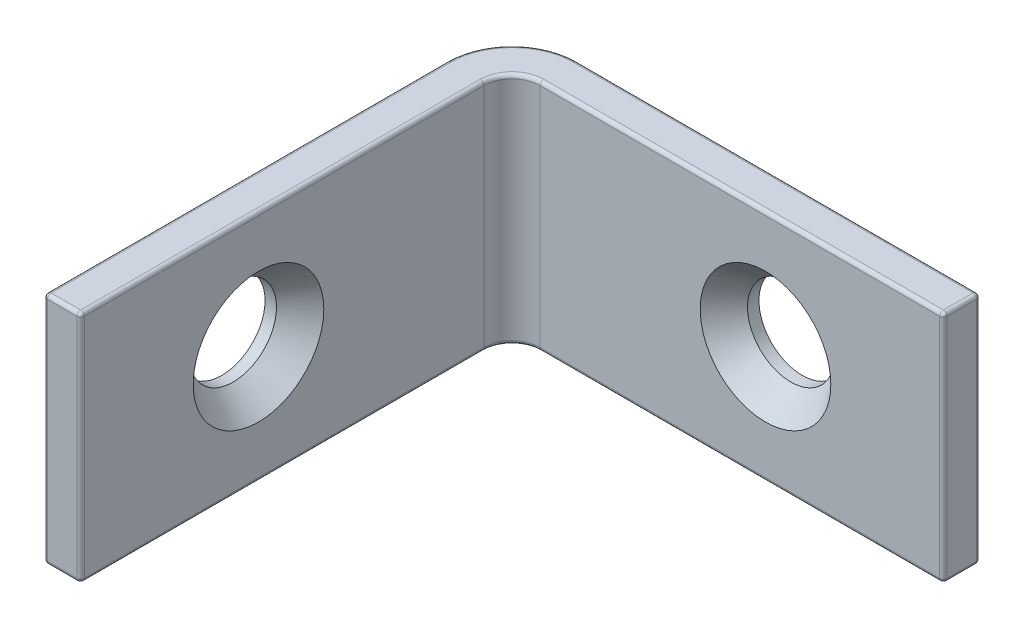
SolidWorks part; units mm, degrees
ref_plane "Front Plane" through (0, 0, 0) normal (0, 0, 1) x (1, 0, 0)
ref_plane "Top Plane" through (0, 0, 0) normal (0, 1, 0) x (1, 0, 0)
ref_plane "Right Plane" through (0, 0, 0) normal (1, 0, 0) x (0, 0, -1)
sketch "Sketch1" plane through (0, 0, 0) normal (0, 0, 1) x (1, 0, 0)
  line L0 (-0.9969, -6.35) -> (-0.9969, 6.35) construction
  line L1 (-0.9969, 6.35) -> (24.403, 6.35) construction
  line L2 (24.403, 6.35) -> (24.403, -6.35) construction
  line L3 (24.403, -6.35) -> (-0.9969, -6.35) construction
  line L4 (0.9969, 6.35) -> (0.9969, -6.35) construction
  line L5 (0.9969, 0) -> (-0.9969, 0) construction
  line L6 (14.751, -3.5433) -> (14.751, 3.5433) construction
  line L7 (12.4015, 0) -> (17.1005, 0) construction
  point P3 (-0.9969, 0)
  point P11 (0, 0)
  point P13 (14.751, 0)
  point P16 (14.751, 0)
  point P19 (14.751, 0)
  dimension "Thickness" = 1.9939
  dimension "Length (B)" = 25.4
  dimension "Length (C)" = 12.7
  dimension "Hole Center" = 9.652
  dimension "Hole Diameter" = 4.699
  dimension "Countersink Diameter" = 7.0866
sketch "Sketch2" plane through (0, 0, 0) normal (1, 0, 0) x (0, 0, -1)
  line L1 (-24.4031, 6.35) -> (0.997, 6.35) construction
  line L2 (-24.4031, 6.35) -> (-24.4031, -6.35) construction
  line L3 (-24.4031, -6.35) -> (0.997, -6.35) construction
  line L4 (0.997, 6.35) -> (0.997, -6.35) construction
  line L5 (-0.997, 6.35) -> (-0.997, -6.35) construction
  line L6 (0.997, 0) -> (-0.997, 0) construction
  point P12 (0, 0)
  point P13 (-14.7511, 0)
  dimension "Length (A)" = 25.4
  dimension "D1" = 1.9939
  dimension "Hole Center 2" = 9.652
sketch "Sketch3" plane through (0, 0, 0) normal (0, 1, 0) x (1, 0, 0)
  line L0 (0.9969, -24.4031) -> (-0.9969, -24.4031)
  line L2 (-0.9969, -24.4031) -> (-0.9969, 0.997)
  line L3 (-0.9969, 0.997) -> (24.403, 0.997)
  line L4 (24.403, -0.997) -> (24.403, 0.997)
  line L6 (24.403, -0.997) -> (0.9969, -0.997)
  line L7 (0.9969, -0.997) -> (0.9969, -24.4031)
  point P3 (0, -24.4031)
  point P8 (24.403, 0)
extrude "Boss-Extrude1" add sketch "Sketch3" along normal mid plane 12.7
fillet "Fillet1" radius 1.524 1 edges at (0.9969, 0, 0.997)
fillet "Fillet2" radius 3.5179 1 edges at (-0.9969, 0, -0.997)
sketch "Sketch4" plane through (0, 0, 0.997) normal (0, 0, 1) x (1, 0, 0)
  line L0 (14.751, 0) -> (16.4124, -1.6613) construction
  line L1 (24.403, 6.35) -> (24.403, -6.35) construction
  circle A0 centre (14.751, 0) radius 2.3495
  dimension "D1" = 45
extrude "Cut-Extrude1" cut sketch "Sketch4" against normal up to next
sketch "Sketch5" plane through (0, 0, 0.997) normal (0, 0, 1) x (1, 0, 0)
  circle A0 centre (14.751, 0) radius 3.5433
extrude "Cut-Extrude2" cut sketch "Sketch5" against normal through all draft 41
sketch "Sketch6" plane through (0.9969, 0, 0) normal (1, 0, 0) x (0, 0, -1)
  circle A0 centre (-14.7511, 0) radius 2.3495
  dimension "D1" = 4.699
extrude "Cut-Extrude3" cut sketch "Sketch6" against normal up to next
sketch "Sketch7" plane through (0.9969, 0, 0) normal (1, 0, 0) x (0, 0, -1)
  circle A0 centre (-14.7511, 0) radius 3.5433
  dimension "D1" = 7.0866
extrude "Cut-Extrude4" cut sketch "Sketch7" against normal through all draft 41
fillet "Fillet3" radius 0.1994 20 edges at (24.403, 0, 0.997) (24.403, 0, -0.997) (-0.9969, 0, 24.4031) (0.9969, 0, 24.4031) (0, -6.35, 24.4031) (0.9969, -6.35, 13.462) (1.4433, -6.35, 1.4433) (13.462, -6.35, 0.997) (24.403, -6.35, 0) (13.462, -6.35, -0.997) (0.0334, -6.35, 0.0334) (-0.9969, -6.35, 13.462) (24.403, 6.35, 0) (13.462, 6.35, 0.997) (1.4433, 6.35, 1.4433) (0.9969, 6.35, 13.462) (0, 6.35, 24.4031) (-0.9969, 6.35, 13.462) (0.0334, 6.35, 0.0334) (13.462, 6.35, -0.997)
equation "\"D1@Sketch2\"=\"Thickness@Sketch1\""
equation "\"D1@Boss-Extrude1\"=\"Length (C)@Sketch1\""
equation "\"D1@Sketch6\"=\"Hole Diameter@Sketch1\""
equation "\"D1@Sketch7\"=\"Countersink Diameter@Sketch1\""
equation "\"D1@Fillet2\"=\"D1@Fillet1\"+\"Thickness@Sketch1\""
equation "\"D1@Fillet3\"=\"Thickness@Sketch1\"*0.1"
